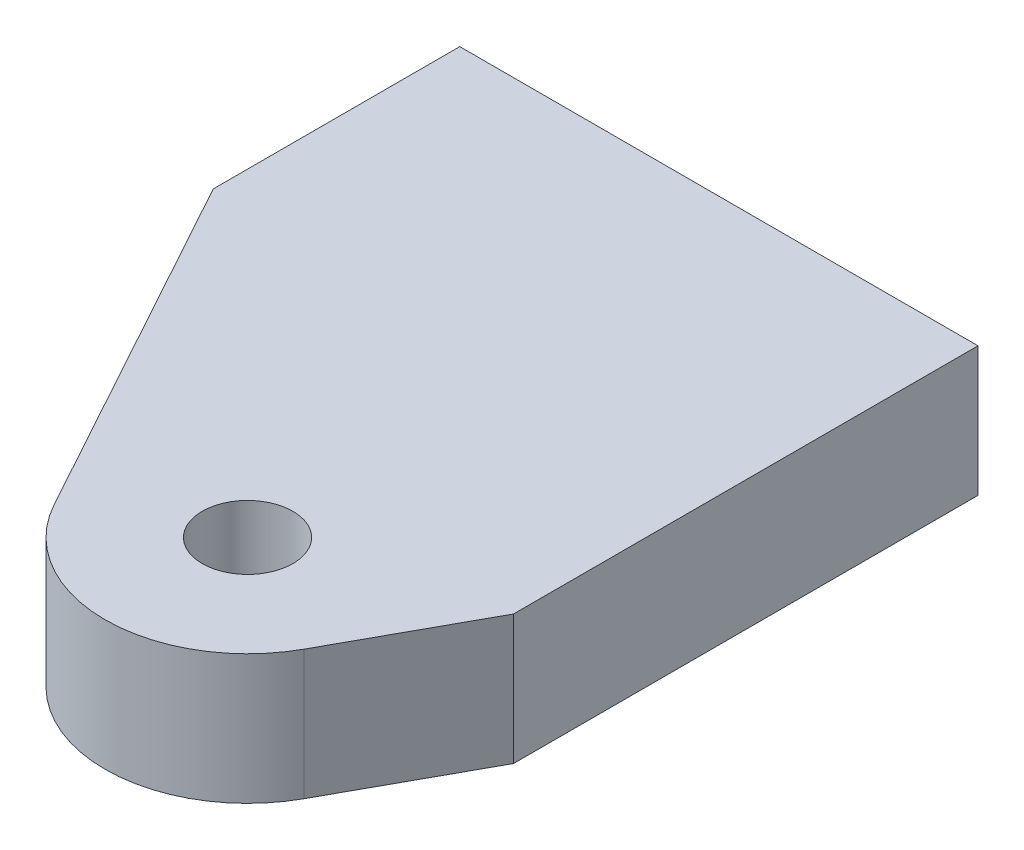
SolidWorks part; units mm, degrees
ref_plane "Front Plane" through (0, 0, 0) normal (0, 0, 1) x (1, 0, 0)
ref_plane "Top Plane" through (0, 0, 0) normal (0, 1, 0) x (1, 0, 0)
ref_plane "Right Plane" through (0, 0, 0) normal (1, 0, 0) x (0, 0, -1)
sketch "Sketch1" plane through (0, 0, 0) normal (0, 1, 0) x (1, 0, 0)
  line L0 (-10, 0) -> (10, 0)
  line L1 (-10, 0) -> (-10, -9.5135)
  line L3 (10, -17.9242) -> (10, 0)
  line L4 (-10, -9.5135) -> (-2.5106, -23.148)
  line L5 (7.1306, -23.148) -> (10, -17.9242)
  arc A0 (-2.5106, -23.148) -> (7.1306, -23.148) centre (2.31, -20.5) ccw
  circle A1 centre (2.31, -20.5) radius 1.75
  point P3 (0, 0)
  point P9 (-1.7148, -11.22)
  point P11 (2.1153, -20.324)
  point P12 (2.31, -20.5)
  point P14 (2.31, -20.5)
  dimension "D2" = 3.5
  dimension "D3" = 5.5
  dimension "D1" = 20
  dimension "D4" = 20.5
  dimension "D5" = 7.69
  dimension "D6" = 151.22
  dimension "D7" = 151.22
extrude "Boss-Extrude1" add sketch "Sketch1" along normal blind 5
equation "\"D7@Sketch1\"=\"D6@Sketch1\""
